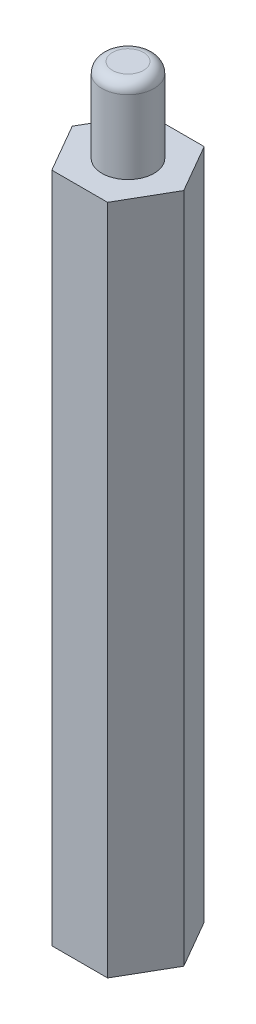
SolidWorks part; units mm, degrees
ref_plane "Alzado" through (0, 0, 0) normal (0, 0, 1) x (1, 0, 0)
ref_plane "Planta" through (0, 0, 0) normal (0, 1, 0) x (1, 0, 0)
ref_plane "Vista lateral" through (0, 0, 0) normal (1, 0, 0) x (0, 0, -1)
sketch "Croquis base" plane through (0, 0, 0) normal (0, 1, 0) x (1, 0, 0)
  line L1 (2.6558, 0) -> (1.3279, 2.3)
  line L2 (1.3279, 2.3) -> (-1.3279, 2.3)
  line L3 (-1.3279, 2.3) -> (-2.6558, 0)
  line L4 (-2.6558, 0) -> (-1.3279, -2.3)
  line L5 (-1.3279, -2.3) -> (1.3279, -2.3)
  line L6 (1.3279, -2.3) -> (2.6558, 0)
  circle A0 centre (0, 0) radius 2.3 construction
extrude "Saliente-Extruir1" add sketch "Croquis base" along normal blind 32
sketch "Croquis Superior" plane through (0, 32, 0) normal (0, 1, 0) x (1, 0, 0)
  circle A0 centre (0, 0) radius 1.24
  dimension "D1" = 2.48
extrude "Saliente-Extruir2" add sketch "Croquis Superior" along normal blind 4
fillet "Redondeo1" radius 0.5 1 edges at (0, 36, 1.24)
sketch "Croquis inferior" plane through (0, 0, 0) normal (0, -1, 0) x (-1, 0, 0)
  circle A0 centre (0, 0) radius 1.25
extrude "Cortar-Extruir1" cut sketch "Croquis inferior" against normal blind 4
